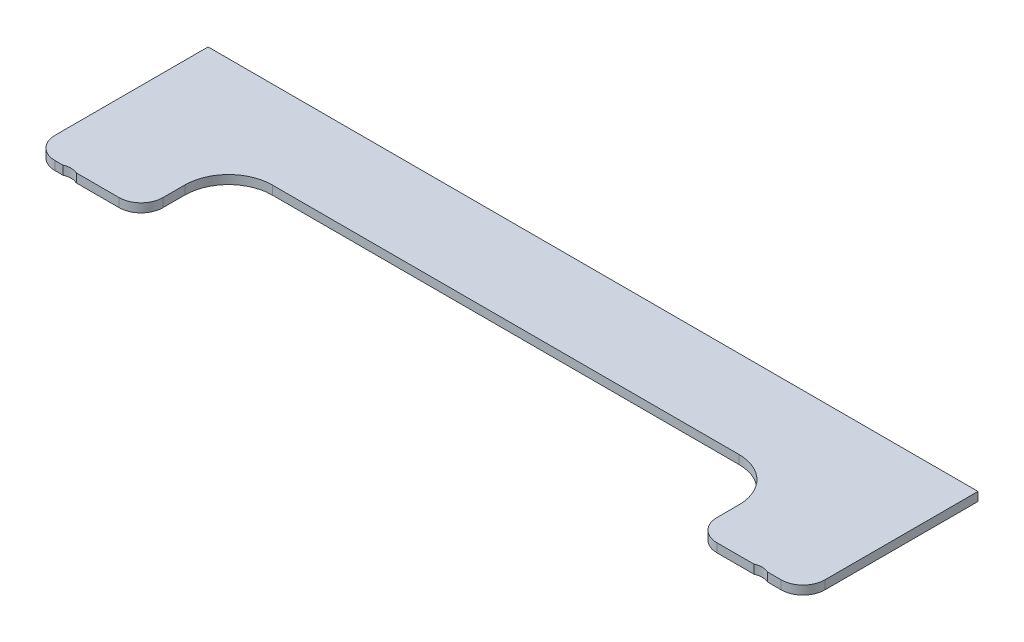
SolidWorks part; units mm, degrees
material "Клен"
ref_plane "Спереди" through (0, 0, 0) normal (0, 0, 1) x (1, 0, 0)
ref_plane "Сверху" through (0, 0, 0) normal (0, 1, 0) x (1, 0, 0)
ref_plane "Справа" through (0, 0, 0) normal (1, 0, 0) x (0, 0, -1)
sketch "Эскиз1" plane through (0, 0, 0) normal (0, 1, 0) x (1, 0, 0)
  line L0 (-338.2029, 15) -> (-338.2029, 120)
  line L5 (-338.2029, 120) -> (189.7971, 120)
  line L6 (189.7971, 120) -> (189.7971, 15)
  line L7 (174.7971, 0) -> (130.7971, 0)
  line L8 (115.7971, 15) -> (115.7971, 30)
  line L9 (85.7971, 60) -> (-234.2029, 60)
  line L10 (-264.2029, 30) -> (-264.2029, 15)
  line L11 (-279.2029, 0) -> (-323.2029, 0)
  arc A0 (-234.2029, 60) -> (-264.2029, 30) centre (-234.2029, 30) ccw
  arc A1 (115.7971, 30) -> (85.7971, 60) centre (85.7971, 30) ccw
  arc A2 (-264.2029, 15) -> (-279.2029, 0) centre (-279.2029, 15) cw
  arc A3 (130.7971, 0) -> (115.7971, 15) centre (130.7971, 15) cw
  arc A4 (-338.2029, 15) -> (-323.2029, 0) centre (-323.2029, 15) ccw
  arc A5 (189.7971, 15) -> (174.7971, 0) centre (174.7971, 15) cw
  point P10 (-264.2029, 22.5)
  point P13 (115.7971, 22.5)
  dimension "D4" = 30
  dimension "D5" = 30
  dimension "D6" = 15
  dimension "D7" = 15
  dimension "D8" = 15
  dimension "D9" = 15
  dimension "D2" = 120
  dimension "D3" = 74
  dimension "D10" = 60
  dimension "D11" = 380
  dimension "D12" = 74
extrude "Бобышка-Вытянуть1" add sketch "Эскиз1" along normal blind 6
sketch "Эскиз7" plane through (0, 0, 0) normal (0, 1, 0) x (1, 0, 0)
  circle A1 centre (-313.2029, -10) radius 11
  dimension "D1" = 22
extrude "Вырез-Вытянуть1" cut sketch "Эскиз7" against normal blind 5 and the other way blind 14
sketch "Эскиз8" plane through (0, 0, 0) normal (0, 1, 0) x (1, 0, 0)
  circle A0 centre (160.7971, -10) radius 11
  dimension "D1" = 22
extrude "Вырез-Вытянуть2" cut sketch "Эскиз8" against normal blind 5 and the other way blind 11
